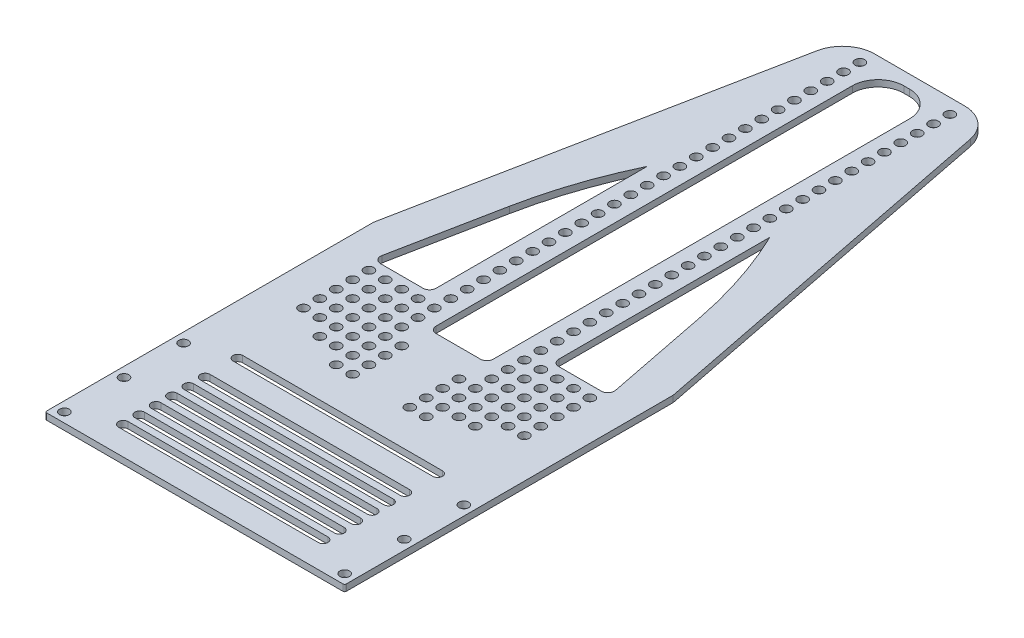
SolidWorks part; units mm, degrees
material "3003 합금"
ref_plane "정면" through (0, 0, 0) normal (0, 0, 1) x (1, 0, 0)
ref_plane "윗면" through (0, 0, 0) normal (0, 1, 0) x (1, 0, 0)
ref_plane "우측면" through (0, 0, 0) normal (1, 0, 0) x (0, 0, -1)
sketch "스케치1" plane through (0, 0, 0) normal (0, 1, 0) x (1, 0, 0)
  line L0 (-13.97, 75) -> (13.97, 75)
  line L1 (-150, -150) -> (150, -150) construction
  line L2 (-150, -150) -> (-150, 150) construction
  line L3 (-150, 150) -> (150, 150) construction
  line L4 (150, -150) -> (150, 150) construction
  line L5 (-0.8906, 70.9664) -> (0.8894, 70.9664)
  line L6 (0, 5.5338) -> (0, -144.4662) construction
  line L7 (-46, -150) -> (46, -150)
  line L8 (36.252, -55.6922) -> (29.7237, -22.6653)
  line L9 (-46.5, -48) -> (-23.7802, 66.9392)
  line L10 (-46.5, -48) -> (-46.5, -149.5)
  line L13 (46.5, -48) -> (46.5, -149.5)
  line L14 (23.7802, 66.9392) -> (46.5, -48)
  line L15 (-19.05, 9.46) -> (-19.05, -56.08)
  line L16 (-31.0159, -137.62) -> (30.9841, -137.62)
  line L18 (-8.89, 62.9664) -> (-8.89, -66.24)
  line L19 (-6.89, -68.24) -> (6.89, -68.24)
  line L20 (8.89, 62.9664) -> (8.89, -66.24)
  line L21 (-31.0159, -142.7) -> (30.9841, -142.7)
  line L22 (-31.0159, -134.62) -> (30.9841, -134.62)
  line L23 (-31.0159, -139.7) -> (30.9841, -139.7)
  line L24 (-31.0159, -137.62) -> (30.9841, -134.62) construction
  line L25 (-13.97, 70.42) -> (-13.97, -50.8622) construction
  line L26 (-43.5, -110) -> (-43.5, -147) construction
  line L27 (-31.0159, -142.7) -> (30.9841, -139.7) construction
  line L28 (13.97, 70.42) -> (13.97, -50.9078) construction
  line L29 (-31.0159, -139.7) -> (30.9841, -142.7) construction
  line L32 (-31.0159, -134.62) -> (30.9841, -137.62) construction
  line L33 (-31.0159, -132.54) -> (30.9841, -132.54)
  line L34 (-31.0159, -129.54) -> (30.9841, -129.54)
  line L35 (-31.0159, -132.54) -> (30.9841, -129.54) construction
  line L36 (-31.0159, -129.54) -> (30.9841, -132.54) construction
  line L37 (-31.0159, -127.46) -> (30.9841, -127.46)
  line L38 (-31.0159, -124.46) -> (30.9841, -124.46)
  line L39 (-31.0159, -127.46) -> (30.9841, -124.46) construction
  line L40 (-31.0159, -124.46) -> (30.9841, -127.46) construction
  line L41 (-31.0159, -122.38) -> (30.9841, -122.38)
  line L42 (-31.0159, -119.38) -> (30.9841, -119.38)
  line L43 (-31.0159, -122.38) -> (30.9841, -119.38) construction
  line L44 (-31.0159, -119.38) -> (30.9841, -122.38) construction
  line L45 (-31.0159, -117.3) -> (30.9841, -117.3)
  line L46 (-31.0159, -114.3) -> (30.9841, -114.3)
  line L47 (-31.0159, -117.3) -> (30.9841, -114.3) construction
  line L48 (-31.0159, -114.3) -> (30.9841, -117.3) construction
  line L49 (-36.252, -55.6922) -> (-29.7237, -22.6653)
  line L50 (-34.29, -58.08) -> (-21.05, -58.08)
  line L52 (19.05, 9.46) -> (19.05, -56.08)
  line L53 (-31.0159, -107.14) -> (30.9841, -107.14)
  line L54 (-31.0159, -104.14) -> (30.9841, -104.14)
  line L55 (-31.0159, -107.14) -> (30.9841, -104.14) construction
  line L56 (-31.0159, -104.14) -> (30.9841, -107.14) construction
  line L58 (34.29, -58.08) -> (21.05, -58.08)
  line L63 (-31.0159, -112.22) -> (30.9841, -112.22) [skipped]
  line L64 (-31.0159, -109.22) -> (30.9841, -109.22) [skipped]
  line L65 (-31.0159, -112.22) -> (30.9841, -109.22) construction
  line L66 (-31.0159, -109.22) -> (30.9841, -112.22) construction
  circle A0 centre (-13.97, 65.34) radius 1.5
  circle A1 centre (-13.97, 60.26) radius 1.5
  circle A2 centre (-13.97, 70.42) radius 1.5
  circle A3 centre (-13.97, 55.18) radius 1.5
  arc A4 (13.97, 75) -> (23.7802, 66.9392) centre (13.97, 65) cw
  arc A5 (-13.97, 75) -> (-23.7802, 66.9392) centre (-13.97, 65) ccw
  circle A6 centre (-13.97, 50.1) radius 1.5
  circle A7 centre (-13.97, 45.02) radius 1.5
  circle A8 centre (-13.97, 39.94) radius 1.5
  circle A9 centre (-13.97, 34.86) radius 1.5
  circle A10 centre (-13.97, 29.78) radius 1.5
  circle A11 centre (-13.97, 24.7) radius 1.5
  circle A12 centre (-13.97, 19.62) radius 1.5
  circle A13 centre (-13.97, 14.54) radius 1.5
  circle A14 centre (-13.97, 9.46) radius 1.5
  circle A15 centre (-13.97, 4.38) radius 1.5
  circle A16 centre (-13.97, -0.7) radius 1.5
  circle A17 centre (-13.97, -5.78) radius 1.5
  circle A18 centre (-13.97, -10.86) radius 1.5
  circle A19 centre (-13.97, -15.94) radius 1.5
  circle A20 centre (-13.97, -21.02) radius 1.5
  circle A21 centre (-13.97, -26.1) radius 1.5
  circle A22 centre (-13.97, -31.18) radius 1.5
  circle A23 centre (-13.97, -36.26) radius 1.5
  circle A24 centre (-13.97, -41.34) radius 1.5
  circle A25 centre (-13.97, -46.42) radius 1.5
  circle A26 centre (-13.97, -51.5) radius 1.5
  circle A27 centre (-13.97, -56.58) radius 1.5
  circle A28 centre (-13.97, -61.66) radius 1.5
  circle A29 centre (-13.97, -66.74) radius 1.5
  circle A30 centre (-13.97, -71.82) radius 1.5
  circle A31 centre (-13.97, -76.9) radius 1.5
  circle A32 centre (-13.97, -81.98) radius 1.5
  circle A33 centre (-13.97, -87.06) radius 1.5
  circle A34 centre (-13.97, -92.14) radius 1.5
  circle A35 centre (-19.05, -61.66) radius 1.5
  circle A36 centre (-19.05, -66.74) radius 1.5
  circle A37 centre (-19.05, -71.82) radius 1.5
  circle A38 centre (-19.05, -76.9) radius 1.5
  circle A39 centre (-19.05, -81.98) radius 1.5
  circle A40 centre (-19.05, -87.06) radius 1.5
  circle A42 centre (-24.13, -61.66) radius 1.5
  circle A43 centre (-24.13, -66.74) radius 1.5
  circle A44 centre (-24.13, -71.82) radius 1.5
  circle A45 centre (-24.13, -76.9) radius 1.5
  circle A46 centre (-24.13, -81.98) radius 1.5
  circle A47 centre (-24.13, -87.06) radius 1.5
  circle A49 centre (-29.21, -61.66) radius 1.5
  circle A50 centre (-29.21, -66.74) radius 1.5
  circle A51 centre (-29.21, -71.82) radius 1.5
  circle A52 centre (-29.21, -76.9) radius 1.5
  circle A53 centre (-29.21, -81.98) radius 1.5
  arc A54 (8.89, 62.9664) -> (0.8894, 70.9664) centre (0.89, 62.9664) ccw
  arc A55 (-8.89, 62.9664) -> (-0.8906, 70.9664) centre (-0.89, 62.9664) cw
  circle A57 centre (-8.89, -76.9) radius 1.5
  circle A58 centre (-34.29, -61.66) radius 1.5
  circle A59 centre (-34.29, -66.74) radius 1.5
  circle A60 centre (-34.29, -71.82) radius 1.5
  circle A61 centre (-34.29, -76.9) radius 1.5
  circle A62 centre (-8.89, -81.98) radius 1.5
  circle A63 centre (-8.89, -87.06) radius 1.5
  circle A64 centre (-8.89, -92.14) radius 1.5
  circle A70 centre (13.97, 39.94) radius 1.5
  circle A71 centre (13.97, 45.02) radius 1.5
  circle A72 centre (13.97, 50.1) radius 1.5
  circle A73 centre (13.97, 55.18) radius 1.5
  circle A74 centre (13.97, 70.42) radius 1.5
  circle A75 centre (13.97, 60.26) radius 1.5
  circle A76 centre (13.97, 65.34) radius 1.5
  arc A77 (29.7237, -22.6653) -> (19.05, 9.46) centre (-102.8024, -48.8615) ccw
  circle A78 centre (13.97, -41.34) radius 1.5
  circle A79 centre (13.97, -36.26) radius 1.5
  circle A80 centre (13.97, -31.18) radius 1.5
  circle A81 centre (13.97, -26.1) radius 1.5
  circle A82 centre (13.97, -21.02) radius 1.5
  circle A83 centre (13.97, -15.94) radius 1.5
  circle A84 centre (13.97, -10.86) radius 1.5
  circle A85 centre (13.97, -5.78) radius 1.5
  circle A86 centre (13.97, -0.7) radius 1.5
  circle A87 centre (13.97, 4.38) radius 1.5
  arc A88 (-31.0159, -142.7) -> (-31.0159, -139.7) centre (-31, -141.2) cw
  arc A89 (30.9841, -142.7) -> (30.9841, -139.7) centre (31, -141.2) ccw
  arc A90 (-31.0159, -137.62) -> (-31.0159, -134.62) centre (-31, -136.12) cw
  arc A91 (30.9841, -137.62) -> (30.9841, -134.62) centre (31, -136.12) ccw
  arc A92 (-31.0159, -132.54) -> (-31.0159, -129.54) centre (-31, -131.04) cw
  arc A93 (30.9841, -132.54) -> (30.9841, -129.54) centre (31, -131.04) ccw
  arc A94 (-31.0159, -127.46) -> (-31.0159, -124.46) centre (-31, -125.96) cw
  arc A95 (30.9841, -127.46) -> (30.9841, -124.46) centre (31, -125.96) ccw
  circle A96 centre (-43.5, -147) radius 1.5
  circle A97 centre (-43.5, -110) radius 1.5
  circle A98 centre (-43.5, -128.5) radius 1.5
  circle A99 centre (43.5, -147) radius 1.5
  circle A100 centre (43.5, -128.5) radius 1.5
  circle A101 centre (43.5, -110) radius 1.5
  arc A102 (-31.0159, -122.38) -> (-31.0159, -119.38) centre (-31, -120.88) cw
  arc A103 (30.9841, -122.38) -> (30.9841, -119.38) centre (31, -120.88) ccw
  arc A104 (-31.0159, -117.3) -> (-31.0159, -114.3) centre (-31, -115.8) cw
  arc A105 (30.9841, -117.3) -> (30.9841, -114.3) centre (31, -115.8) ccw
  circle A106 centre (13.97, 9.46) radius 1.5
  circle A107 centre (13.97, 14.54) radius 1.5
  arc A108 (-31.0159, -107.14) -> (-31.0159, -104.14) centre (-31, -105.64) cw
  arc A109 (30.9841, -107.14) -> (30.9841, -104.14) centre (31, -105.64) ccw
  circle A110 centre (13.97, 19.62) radius 1.5
  circle A111 centre (13.97, 24.7) radius 1.5
  circle A112 centre (13.97, 29.78) radius 1.5
  circle A113 centre (13.97, 34.86) radius 1.5
  circle A114 centre (13.97, -66.74) radius 1.5
  circle A115 centre (34.29, -66.74) radius 1.5
  circle A116 centre (29.21, -66.74) radius 1.5
  circle A117 centre (24.13, -66.74) radius 1.5
  circle A118 centre (19.05, -66.74) radius 1.5
  arc A119 (19.05, -56.08) -> (21.05, -58.08) centre (21.05, -56.08) ccw
  arc A120 (36.252, -55.6922) -> (34.29, -58.08) centre (34.29, -56.08) cw
  circle A121 centre (34.29, -61.66) radius 1.5
  circle A122 centre (29.21, -61.66) radius 1.5
  circle A123 centre (24.13, -61.66) radius 1.5
  circle A124 centre (19.05, -61.66) radius 1.5
  circle A125 centre (13.97, -61.66) radius 1.5
  circle A126 centre (13.97, -56.58) radius 1.5
  circle A127 centre (13.97, -51.5) radius 1.5
  circle A128 centre (13.97, -46.42) radius 1.5
  circle A134 centre (8.89, -92.14) radius 1.5
  arc A135 (-31.0159, -112.22) -> (-31.0159, -109.22) centre (-31, -110.72) cw [skipped]
  arc A136 (30.9841, -112.22) -> (30.9841, -109.22) centre (31, -110.72) ccw [skipped]
  circle A137 centre (8.89, -87.06) radius 1.5
  arc A138 (-8.89, -66.24) -> (-6.89, -68.24) centre (-6.89, -66.24) ccw
  arc A139 (6.89, -68.24) -> (8.89, -66.24) centre (6.89, -66.24) ccw
  arc A140 (-29.7237, -22.6653) -> (-19.05, 9.46) centre (102.8024, -48.8615) cw
  arc A141 (-36.252, -55.6922) -> (-34.29, -58.08) centre (-34.29, -56.08) ccw
  circle A142 centre (8.89, -81.98) radius 1.5
  circle A143 centre (34.29, -76.9) radius 1.5
  circle A144 centre (34.29, -71.82) radius 1.5
  circle A145 centre (8.89, -76.9) radius 1.5
  arc A146 (-19.05, -56.08) -> (-21.05, -58.08) centre (-21.05, -56.08) cw
  circle A149 centre (29.21, -76.9) radius 1.5
  circle A150 centre (29.21, -71.82) radius 1.5
  circle A152 centre (24.13, -87.06) radius 1.5
  circle A153 centre (24.13, -81.98) radius 1.5
  circle A154 centre (24.13, -76.9) radius 1.5
  circle A155 centre (24.13, -71.82) radius 1.5
  circle A157 centre (19.05, -87.06) radius 1.5
  circle A158 centre (19.05, -81.98) radius 1.5
  circle A159 centre (19.05, -76.9) radius 1.5
  circle A160 centre (19.05, -71.82) radius 1.5
  circle A161 centre (13.97, -92.14) radius 1.5
  circle A162 centre (13.97, -87.06) radius 1.5
  circle A163 centre (13.97, -81.98) radius 1.5
  circle A164 centre (13.97, -76.9) radius 1.5
  circle A165 centre (13.97, -71.82) radius 1.5
  circle A168 centre (-34.29, -81.98) radius 1.5
  circle A172 centre (34.29, -81.98) radius 1.5
  circle A175 centre (29.21, -81.98) radius 1.5
  arc A176 (-46.5, -149.5) -> (-46, -150) centre (-46, -149.5) ccw
  arc A177 (46, -150) -> (46.5, -149.5) centre (46, -149.5) ccw
  circle A185 centre (-34.29, -81.98) radius 1.5 [skipped]
  circle A186 centre (-34.29, -87.06) radius 1.5 [skipped]
  circle A187 centre (-34.29, -92.14) radius 1.5 [skipped]
  circle A188 centre (-29.21, -87.06) radius 1.5 [skipped]
  circle A189 centre (-29.21, -92.14) radius 1.5 [skipped]
  circle A190 centre (-29.21, -81.98) radius 1.5 [skipped]
  circle A191 centre (-8.89, -71.82) radius 1.5 [skipped]
  circle A192 centre (-3.81, -71.82) radius 1.5 [skipped]
  circle A193 centre (-3.81, -76.9) radius 1.5 [skipped]
  circle A194 centre (-3.81, -81.98) radius 1.5 [skipped]
  circle A195 centre (-3.81, -87.06) radius 1.5 [skipped]
  circle A196 centre (-3.81, -92.14) radius 1.5 [skipped]
  circle A197 centre (-19.05, -92.14) radius 1.5 [skipped]
  circle A198 centre (-24.13, -92.14) radius 1.5 [skipped]
  circle A199 centre (-29.21, -87.06) radius 1.5 [skipped]
  circle A200 centre (-34.29, -87.06) radius 1.5 [skipped]
  point P0 (0, 0)
  point P8 (-0.0159, -141.2)
  point P17 (0, 70)
  point P23 (-46.5, -150)
  point P24 (0, 75)
  point P215 (-0.0159, -110.72)
  point P217 (-0.0159, -136.12)
  point P224 (-0.0159, -131.04)
  point P241 (-0.0159, -125.96)
  point P248 (-0.0159, -120.88)
  point P255 (-0.0159, -115.8)
  point P269 (-0.0159, -105.64)
  dimension "D11" = 5.08
  dimension "D14" = 3
  dimension "D16" = 2
  dimension "D21" = 8
  dimension "D23" = 2
  dimension "D24" = 17.78
  dimension "D28" = 3
  dimension "D30" = 3
  dimension "D43" = 5.08
  dimension "D25" = 27.94
  dimension "D31" = 3
  dimension "D40" = 3
  dimension "D41" = 18.5
  dimension "D13" = 5.08
  dimension "D37" = 2.86
  dimension "D36" = 8
  dimension "D38" = 62
  dimension "D6" = 10
  dimension "D35" = 3
  dimension "D7" = 0.5
  dimension "D19" = 5.08
  dimension "D56" = 150.7
  dimension "D60" = 2
  dimension "D61" = 46.5
  dimension "D5" = 102
  dimension "D8" = 33
  dimension "D9" = 7.3
  dimension "D12" = 5
  dimension "D15" = 27.94
  dimension "D17" = 3
  dimension "D22" = 17.78
  dimension "D29" = 3
  dimension "D33" = 18.5
  dimension "D34" = 18.5
  dimension "D45" = 5.08
  dimension "D27" = 93
  dimension "D39" = 3
  dimension "3" = 3
  dimension "D48" = 4.58
  dimension "D49" = 225
  dimension "D50" = 8.66
  dimension "D51" = 8.66
  dimension "D55" = 5.08
  dimension "D57" = 150
  dimension "D58" = 150
  dimension "D59" = 31
  dimension "D32" = 2
  dimension "D18" = 3
extrude "보스-돌출1" add sketch "스케치1" along normal blind 2
